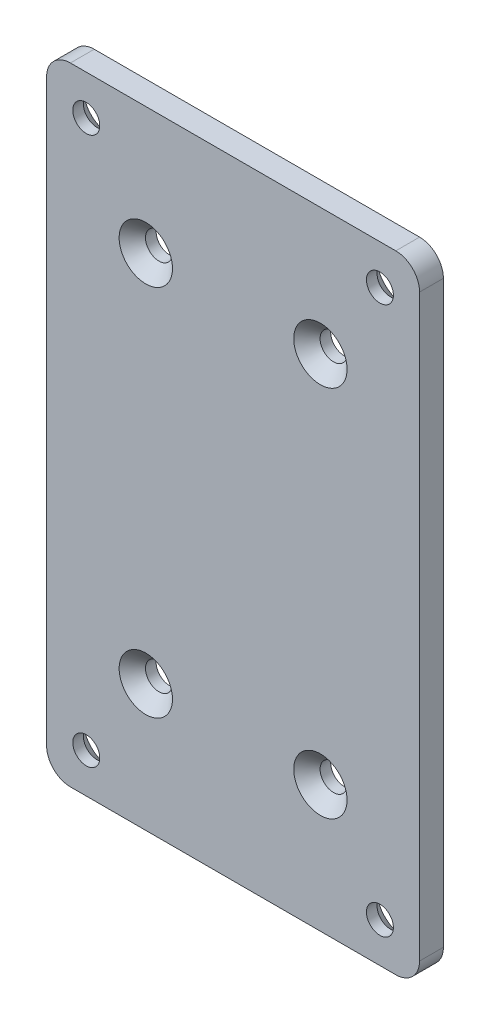
SolidWorks part; units mm, degrees
ref_plane "Спереди" through (0, 0, 0) normal (0, 0, 1) x (1, 0, 0)
ref_plane "Сверху" through (0, 0, 0) normal (0, 1, 0) x (1, 0, 0)
ref_plane "Справа" through (0, 0, 0) normal (1, 0, 0) x (0, 0, -1)
sketch "Эскиз1" plane through (0, 0, 0) normal (0, 0, 1) x (1, 0, 0)
  line L1 (-23.5, 39.5) -> (23.5, 39.5)
  line L2 (-23.5, 39.5) -> (-23.5, -39.5)
  line L3 (-23.5, -39.5) -> (23.5, -39.5)
  line L4 (23.5, 39.5) -> (23.5, -39.5)
  line L5 (-23.5, 39.5) -> (23.5, -39.5) construction
  line L6 (-23.5, -39.5) -> (23.5, 39.5) construction
  point P0 (0, 0)
  dimension "D1" = 47
  dimension "D2" = 79
extrude "Бобышка-Вытянуть1" add sketch "Эскиз1" along normal blind 3
sketch "Эскиз2" plane through (0, 0, 3) normal (0, 0, 1) x (1, 0, 0)
  line L1 (-11, 23.5) -> (11, 23.5) construction
  line L2 (-11, 23.5) -> (-11, -23.5) construction
  line L3 (-11, -23.5) -> (11, -23.5) construction
  line L4 (11, 23.5) -> (11, -23.5) construction
  line L5 (-11, 23.5) -> (11, -23.5) construction
  line L6 (-11, -23.5) -> (11, 23.5) construction
  point P0 (0, 0)
  dimension "D1" = 22
  dimension "D2" = 47
hole_wizard "Зенковка для  винта с потайной головкой с внутренним шестигранником M31" positions "Эскиз4" profile "Эскиз3" countersink size "M3" standard "Ansi Metric" end condition through all
sketch "Эскиз4" plane through (0, 0, 3) normal (0, 0, 1) x (1, 0, 0)
  point P0 (-11, 23.5)
  point P3 (11, 23.5)
  point P6 (-11, -23.5)
  point P9 (11, -23.5)
sketch "Эскиз3" plane through (-11, 23.5, 3) normal (1, 0, 0) x (0, -1, 0)
  line L0 (0, 0) -> (0, 3)
  line L1 (0, 3) -> (1.7, 3)
  line L2 (1.7, 3) -> (1.7, 1.66)
  line L3 (1.7, 1.66) -> (3.36, 0)
  line L5 (3.36, 0) -> (0, 0)
  line L6 (-1.7, 1.66) -> (-3.36, 0) construction
  line L11 (0, -6.35) -> (0, 107.95) construction
  dimension "Диаметр сквозного отверстия" = 3.4
  dimension "Глубина сквозного отверстия" = 3
  dimension "Диаметр передней зенковки" = 6.72
  dimension "Угол передней зенковки" = 90
sketch "Эскиз5" plane through (0, 0, 0) normal (0, 0, -1) x (-1, 0, 0)
  line L0 (-23.5, -39.5) -> (-23.5, 39.5) construction
  line L1 (-18.5, 34.5) -> (18.5, 34.5) construction
  line L2 (-18.5, 34.5) -> (-18.5, -34.5) construction
  line L3 (-18.5, -34.5) -> (18.5, -34.5) construction
  line L4 (18.5, 34.5) -> (18.5, -34.5) construction
  line L5 (-18.5, 34.5) -> (18.5, -34.5) construction
  line L6 (-18.5, -34.5) -> (18.5, 34.5) construction
  line L7 (-23.5, 39.5) -> (23.5, 39.5) construction
  point P0 (0, 0)
  dimension "D1" = 5
  dimension "D2" = 5
hole_wizard "Зенковка для  винта с потайной головкой с внутренним шестигранником M32" positions "Эскиз7" profile "Эскиз6" countersink size "M3" standard "Ansi Metric" end condition through all
sketch "Эскиз7" plane through (0, 0, 0) normal (0, 0, -1) x (-1, 0, 0)
  point P0 (-18.5, 34.5)
  point P3 (18.5, 34.5)
  point P6 (-18.5, -34.5)
  point P9 (18.5, -34.5)
sketch "Эскиз6" plane through (18.5, 34.5, 0) normal (1, 0, 0) x (0, 1, 0)
  line L0 (0, 0) -> (0, 3)
  line L1 (0, 3) -> (1.7, 3)
  line L2 (1.7, 3) -> (1.7, 1.66)
  line L3 (1.7, 1.66) -> (3.36, 0)
  line L5 (3.36, 0) -> (0, 0)
  line L6 (-1.7, 1.66) -> (-3.36, 0) construction
  line L11 (0, -6.35) -> (0, 107.95) construction
  dimension "Диаметр сквозного отверстия" = 3.4
  dimension "Глубина сквозного отверстия" = 3
  dimension "Диаметр передней зенковки" = 6.72
  dimension "Угол передней зенковки" = 90
fillet "Скругление1" radius 3 4 edges at (-23.5, 39.5, 1.5) (-23.5, -39.5, 1.5) (23.5, -39.5, 1.5) (23.5, 39.5, 1.5)
sketch "Эскиз8" plane through (0, 0, 0) normal (0, 0, 1) x (1, 0, 0)
  line L0 (23.5, -36.5) -> (23.5, 36.5) construction
  line L1 (-20.5, -39.5) -> (20.5, -39.5) construction
  point P0 (23.5, -39.5)
